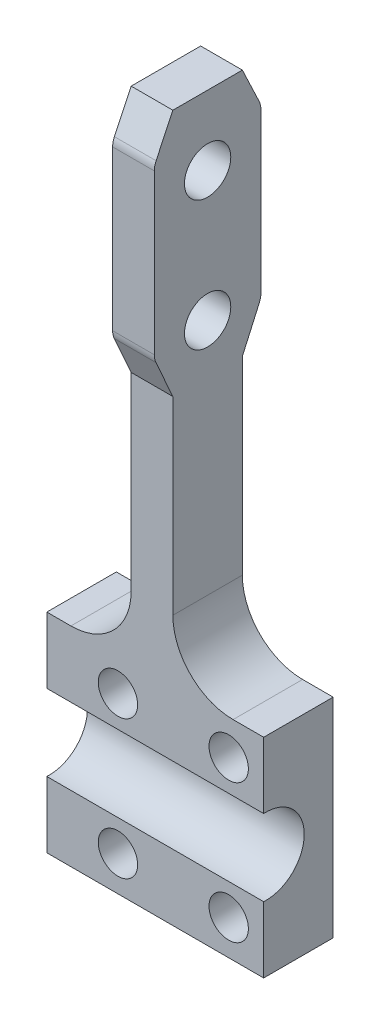
SolidWorks part; units mm, degrees
ref_plane "Front Plane" through (0, 0, 0) normal (0, 0, 1) x (1, 0, 0)
ref_plane "Top Plane" through (0, 0, 0) normal (0, 1, 0) x (1, 0, 0)
ref_plane "Right Plane" through (0, 0, 0) normal (1, 0, 0) x (0, 0, -1)
sketch "Sketch1" plane through (0, 0, 0) normal (0, 0, 1) x (1, 0, 0)
  line L0 (-26.3, 129.9) -> (39.7021, 129.9) construction
  line L1 (-8.1, 22.5) -> (-8.1, 129.9)
  line L3 (0.9, 35.5) -> (0.9, 129.9)
  line L5 (-8.1, 129.9) -> (0.9, 129.9)
  line L12 (-26.3, 22.5) -> (-26.3, -22.5)
  line L13 (-26.3, -22.5) -> (20.5, -22.5)
  line L14 (20.5, -22.5) -> (20.5, 22.5)
  line L15 (20.5, 22.5) -> (13.9, 22.5)
  line L17 (-8.1, 22.5) -> (-26.3, 22.5)
  circle A4 centre (-10.95, -14.95) radius 4.25
  circle A5 centre (12.95, -14.95) radius 4.25
  circle A6 centre (12.95, 14.95) radius 4.25
  circle A7 centre (-10.95, 14.95) radius 4.25
  arc A8 (0.9, 35.5) -> (13.9, 22.5) centre (13.9, 35.5) ccw
  point P32 (-8.1, 22.5)
  dimension "D4" = 13
  dimension "D3" = 9
extrude "Boss-Extrude1" add sketch "Sketch1" along normal blind 15
sketch "Sketch3" plane through (-26.3, 0, 0) normal (-1, 0, 0) x (0, 0, 1)
  line L0 (15, 0) -> (-12.6668, 0) construction
  line L1 (15, 22.5) -> (15, -22.5) construction
  circle A0 centre (14.5, 0) radius 8.25
  dimension "D2" = 16.5
  dimension "D1" = 0.5
extrude "Cut-Extrude1" cut sketch "Sketch3" against normal blind 55.05
sketch "Sketch4" plane through (0.9, 0, 0) normal (1, 0, 0) x (0, 0, -1)
  line L0 (-7.5, 22.5) -> (-7.5, 86.9) construction
  line L1 (-15, 22.5) -> (0, 22.5) construction
  circle A0 centre (-7.5, 86.9) radius 5
  circle A1 centre (-7.5, 114.9) radius 5
  dimension "D1" = 10
  dimension "D2" = 28
extrude "Cut-Extrude3" cut sketch "Sketch4" against normal blind 46.05
sketch "Sketch6" plane through (-8.1, 0, 0) normal (-1, 0, 0) x (0, 0, 1)
  line L0 (15, 76.3869) -> (18.6516, 84.5541)
  line L1 (15, 129.9) -> (15, 22.5) construction
  line L2 (19, 86.1868) -> (19, 120.55)
  line L3 (18.6155, 122.2613) -> (15, 129.9)
  line L4 (7.5, 114.9) -> (7.5, 65.4139) construction
  line L5 (-3.6155, 122.2613) -> (0, 129.9)
  line L6 (-4, 86.1868) -> (-4, 120.55)
  line L7 (0, 76.3869) -> (-3.6516, 84.5541)
  line L8 (0, 76.3869) -> (0, 129.9)
  line L9 (15, 76.3869) -> (15, 129.9)
  arc A0 (19, 120.55) -> (18.6155, 122.2613) centre (15, 120.55) ccw
  arc A1 (18.6516, 84.5541) -> (19, 86.1868) centre (15, 86.1868) ccw
  arc A2 (-3.6516, 84.5541) -> (-4, 86.1868) centre (0, 86.1868) cw
  arc A3 (-4, 120.55) -> (-3.6155, 122.2613) centre (0, 120.55) cw
  dimension "D1" = 4
  dimension "D2" = 4
extrude "Boss-Extrude2" add sketch "Sketch6" against normal up to surface (9 mm away) up to face at (0.9, 86.9, 2.5)
fillet "Fillet1" radius 13 1 edges at (-8.1, 22.5, 7.5)
